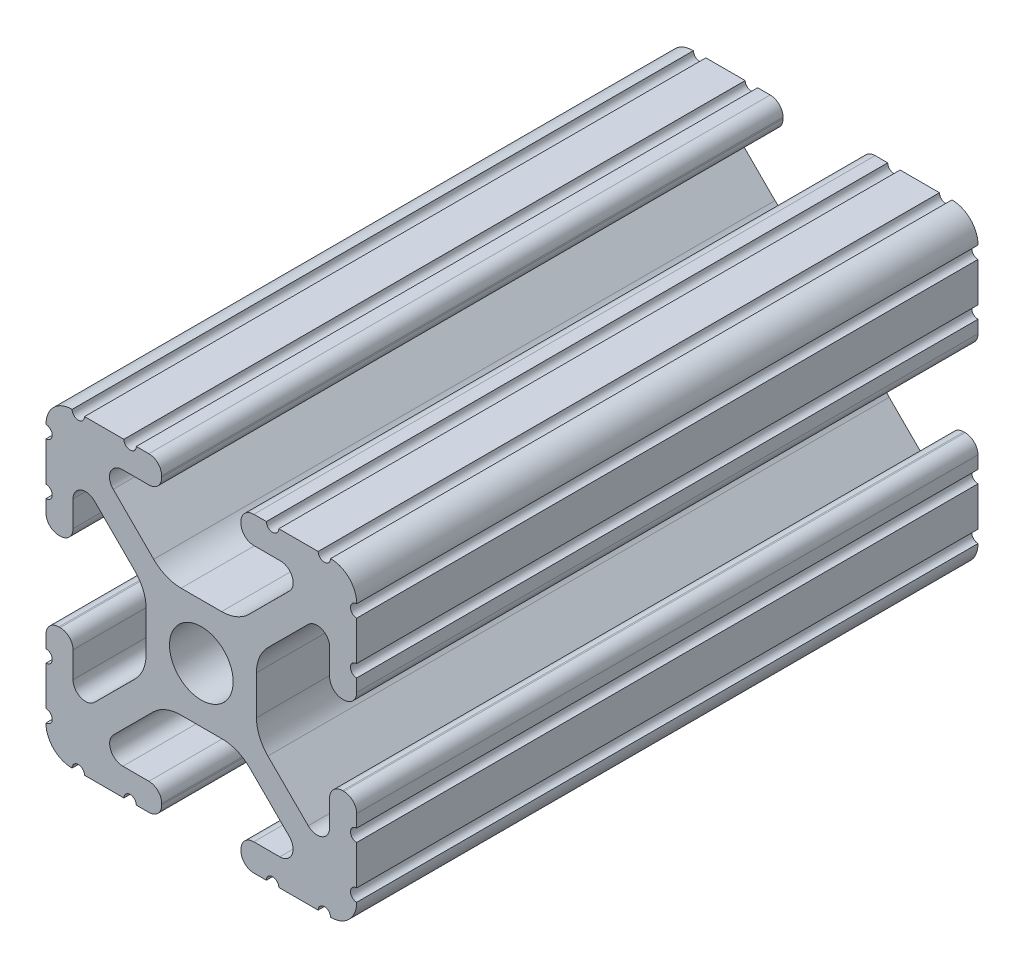
SolidWorks part; units mm, degrees
ref_plane "Front Plane" through (0, 0, 0) normal (0, 0, 1) x (1, 0, 0)
ref_plane "Top Plane" through (0, 0, 0) normal (0, 1, 0) x (1, 0, 0)
ref_plane "Right Plane" through (0, 0, 0) normal (1, 0, 0) x (0, 0, -1)
sketch "Sketch1" plane through (0, 0, 0) normal (0, 0, 1) x (1, 0, 0)
  line L88 (-7.1797, -8.6452) -> (-3.9523, -5.4237)
  line L89 (-1.7093, -4.4958) -> (1.7093, -4.4958)
  line L90 (3.9523, -5.4237) -> (7.1797, -8.6452)
  line L91 (6.4164, -10.4902) -> (4.2875, -10.4902)
  line L92 (3.2385, -11.5392) -> (3.2385, -11.651)
  line L93 (4.2875, -12.7) -> (5.3171, -12.7)
  line L94 (6.3331, -12.7) -> (9.5504, -12.7)
  line L95 (12.7, -9.5504) -> (12.7, -6.3331)
  line L96 (12.7, -5.3171) -> (12.7, -4.2875)
  line L97 (11.651, -3.2385) -> (11.5392, -3.2385)
  line L98 (10.4902, -4.2875) -> (10.4902, -6.4021)
  line L99 (8.7371, -7.1294) -> (5.441, -3.8408)
  line L100 (4.5085, -1.5932) -> (4.5085, 1.5932)
  line L101 (5.441, 3.8408) -> (8.7371, 7.1294)
  line L102 (10.4902, 6.4021) -> (10.4902, 4.2875)
  line L103 (11.5392, 3.2385) -> (11.651, 3.2385)
  line L104 (12.7, 4.2875) -> (12.7, 5.3171)
  line L105 (12.7, 6.3331) -> (12.7, 9.5504)
  line L106 (9.5504, 12.7) -> (6.3331, 12.7)
  line L107 (5.3171, 12.7) -> (4.2875, 12.7)
  line L108 (3.2385, 11.651) -> (3.2385, 11.5392)
  line L109 (4.2875, 10.4902) -> (6.4768, 10.4902)
  line L110 (7.207, 8.7244) -> (3.8983, 5.4232)
  line L111 (1.6558, 4.4958) -> (-1.6558, 4.4958)
  line L112 (-3.8983, 5.4232) -> (-7.207, 8.7244)
  line L113 (-6.4768, 10.4902) -> (-4.2875, 10.4902)
  line L114 (-3.2385, 11.5392) -> (-3.2385, 11.651)
  line L115 (-4.2875, 12.7) -> (-5.3171, 12.7)
  line L116 (-6.3331, 12.7) -> (-9.5504, 12.7)
  line L117 (-12.7, 9.5504) -> (-12.7, 6.3331)
  line L118 (-12.7, 5.3171) -> (-12.7, 4.2875)
  line L119 (-11.651, 3.2385) -> (-11.5392, 3.2385)
  line L120 (-10.4902, 4.2875) -> (-10.4902, 6.4021)
  line L121 (-8.7371, 7.1294) -> (-5.441, 3.8408)
  line L122 (-4.5085, 1.5932) -> (-4.5085, -1.5932)
  line L123 (-5.441, -3.8408) -> (-8.7371, -7.1294)
  line L124 (-10.4902, -6.4021) -> (-10.4902, -4.2875)
  line L125 (-11.5392, -3.2385) -> (-11.651, -3.2385)
  line L126 (-12.7, -4.2875) -> (-12.7, -5.3171)
  line L127 (-12.7, -6.3331) -> (-12.7, -9.5504)
  line L128 (-9.5504, -12.7) -> (-6.3331, -12.7)
  line L129 (-5.3171, -12.7) -> (-4.2875, -12.7)
  line L130 (-3.2385, -11.651) -> (-3.2385, -11.5392)
  line L131 (-4.2875, -10.4902) -> (-6.4164, -10.4902)
  circle A1 centre (0, 0) radius 2.6035
  arc A104 (-7.1797, -8.6452) -> (-6.4164, -10.4902) centre (-6.4164, -9.4098) ccw
  arc A105 (-1.7093, -4.4958) -> (-3.9523, -5.4237) centre (-1.7093, -7.6708) ccw
  arc A106 (3.9523, -5.4237) -> (1.7093, -4.4958) centre (1.7093, -7.6708) ccw
  arc A107 (6.4164, -10.4902) -> (7.1797, -8.6452) centre (6.4164, -9.4098) ccw
  arc A108 (4.2875, -10.4902) -> (3.2385, -11.5392) centre (4.2875, -11.5392) ccw
  arc A109 (3.2385, -11.651) -> (4.2875, -12.7) centre (4.2875, -11.651) ccw
  arc A110 (6.3331, -12.7) -> (5.3171, -12.7) centre (5.8251, -12.7) ccw
  arc A111 (10.5664, -12.6998) -> (9.5504, -12.7) centre (10.0584, -12.7) ccw
  arc A112 (10.5664, -12.6998) -> (12.6998, -10.5664) centre (10.5918, -10.5918) ccw
  arc A113 (12.7, -9.5504) -> (12.6998, -10.5664) centre (12.7, -10.0584) ccw
  arc A114 (12.7, -5.3171) -> (12.7, -6.3331) centre (12.7, -5.8251) ccw
  arc A115 (12.7, -4.2875) -> (11.651, -3.2385) centre (11.651, -4.2875) ccw
  arc A116 (11.5392, -3.2385) -> (10.4902, -4.2875) centre (11.5392, -4.2875) ccw
  arc A117 (8.7371, -7.1294) -> (10.4902, -6.4021) centre (9.4628, -6.4021) ccw
  arc A118 (4.5085, -1.5932) -> (5.441, -3.8408) centre (7.6835, -1.5932) ccw
  arc A119 (5.441, 3.8408) -> (4.5085, 1.5932) centre (7.6835, 1.5932) ccw
  arc A120 (10.4902, 6.4021) -> (8.7371, 7.1294) centre (9.4628, 6.4021) ccw
  arc A121 (10.4902, 4.2875) -> (11.5392, 3.2385) centre (11.5392, 4.2875) ccw
  arc A122 (11.651, 3.2385) -> (12.7, 4.2875) centre (11.651, 4.2875) ccw
  arc A123 (12.7, 6.3331) -> (12.7, 5.3171) centre (12.7, 5.8251) ccw
  arc A124 (12.6998, 10.5664) -> (12.7, 9.5504) centre (12.7, 10.0584) ccw
  arc A125 (12.6998, 10.5664) -> (10.5664, 12.6998) centre (10.5918, 10.5918) ccw
  arc A126 (9.5504, 12.7) -> (10.5664, 12.6998) centre (10.0584, 12.7) ccw
  arc A127 (5.3171, 12.7) -> (6.3331, 12.7) centre (5.8251, 12.7) ccw
  arc A128 (4.2875, 12.7) -> (3.2385, 11.651) centre (4.2875, 11.651) ccw
  arc A129 (3.2385, 11.5392) -> (4.2875, 10.4902) centre (4.2875, 11.5392) ccw
  arc A130 (7.207, 8.7244) -> (6.4768, 10.4902) centre (6.4768, 9.4563) ccw
  arc A131 (1.6558, 4.4958) -> (3.8983, 5.4232) centre (1.6558, 7.6708) ccw
  arc A132 (-3.8983, 5.4232) -> (-1.6558, 4.4958) centre (-1.6558, 7.6708) ccw
  arc A133 (-6.4768, 10.4902) -> (-7.207, 8.7244) centre (-6.4768, 9.4563) ccw
  arc A134 (-4.2875, 10.4902) -> (-3.2385, 11.5392) centre (-4.2875, 11.5392) ccw
  arc A135 (-3.2385, 11.651) -> (-4.2875, 12.7) centre (-4.2875, 11.651) ccw
  arc A136 (-6.3331, 12.7) -> (-5.3171, 12.7) centre (-5.8251, 12.7) ccw
  arc A137 (-10.5664, 12.6998) -> (-9.5504, 12.7) centre (-10.0584, 12.7) ccw
  arc A138 (-10.5664, 12.6998) -> (-12.6998, 10.5664) centre (-10.5918, 10.5918) ccw
  arc A139 (-12.7, 9.5504) -> (-12.6998, 10.5664) centre (-12.7, 10.0584) ccw
  arc A140 (-12.7, 5.3171) -> (-12.7, 6.3331) centre (-12.7, 5.8251) ccw
  arc A141 (-12.7, 4.2875) -> (-11.651, 3.2385) centre (-11.651, 4.2875) ccw
  arc A142 (-11.5392, 3.2385) -> (-10.4902, 4.2875) centre (-11.5392, 4.2875) ccw
  arc A143 (-8.7371, 7.1294) -> (-10.4902, 6.4021) centre (-9.4628, 6.4021) ccw
  arc A144 (-4.5085, 1.5932) -> (-5.441, 3.8408) centre (-7.6835, 1.5932) ccw
  arc A145 (-5.441, -3.8408) -> (-4.5085, -1.5932) centre (-7.6835, -1.5932) ccw
  arc A146 (-10.4902, -6.4021) -> (-8.7371, -7.1294) centre (-9.4628, -6.4021) ccw
  arc A147 (-10.4902, -4.2875) -> (-11.5392, -3.2385) centre (-11.5392, -4.2875) ccw
  arc A148 (-11.651, -3.2385) -> (-12.7, -4.2875) centre (-11.651, -4.2875) ccw
  arc A149 (-12.7, -6.3331) -> (-12.7, -5.3171) centre (-12.7, -5.8251) ccw
  arc A150 (-12.6998, -10.5664) -> (-12.7, -9.5504) centre (-12.7, -10.0584) ccw
  arc A151 (-12.6998, -10.5664) -> (-10.5664, -12.6998) centre (-10.5918, -10.5918) ccw
  arc A152 (-9.5504, -12.7) -> (-10.5664, -12.6998) centre (-10.0584, -12.7) ccw
  arc A153 (-5.3171, -12.7) -> (-6.3331, -12.7) centre (-5.8251, -12.7) ccw
  arc A154 (-4.2875, -12.7) -> (-3.2385, -11.651) centre (-4.2875, -11.651) ccw
  arc A155 (-3.2385, -11.5392) -> (-4.2875, -10.4902) centre (-4.2875, -11.5392) ccw
extrude "Boss-Extrude1" add sketch "Sketch1" along normal mid plane 50.8
